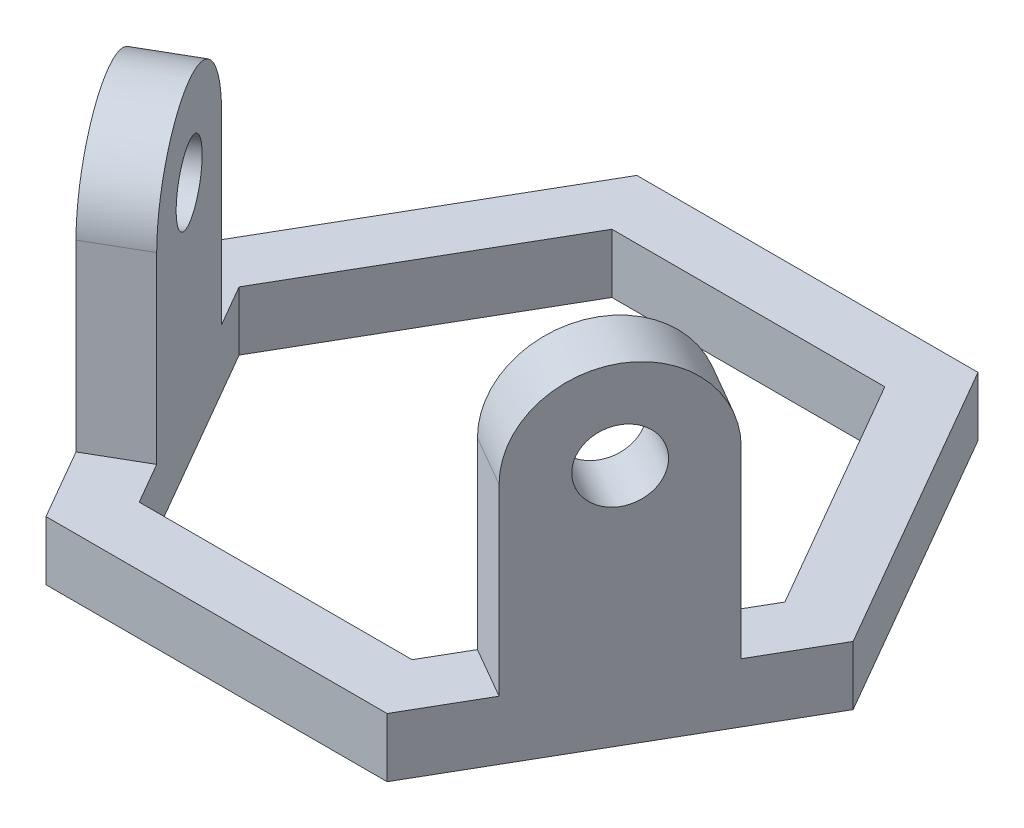
SolidWorks part; units mm, degrees
ref_plane "Front Plane" through (0, 0, 0) normal (0, 0, 1) x (1, 0, 0)
ref_plane "Top Plane" through (0, 0, 0) normal (0, 1, 0) x (1, 0, 0)
ref_plane "Right Plane" through (0, 0, 0) normal (1, 0, 0) x (0, 0, -1)
sketch "Sketch1" plane through (0, 0, 0) normal (0, 1, 0) x (1, 0, 0)
  line L0 (46.188, 0) -> (23.094, 40)
  line L1 (57.735, 0) -> (28.8675, 50)
  line L2 (28.8675, 50) -> (-28.8675, 50)
  line L3 (-28.8675, 50) -> (-57.735, 0)
  line L4 (-57.735, 0) -> (-28.8675, -50)
  line L5 (-28.8675, -50) -> (28.8675, -50)
  line L6 (28.8675, -50) -> (57.735, 0)
  line L7 (23.094, 40) -> (-23.094, 40)
  line L8 (-23.094, 40) -> (-46.188, 0)
  line L9 (-46.188, 0) -> (-23.094, -40)
  line L10 (-23.094, -40) -> (23.094, -40)
  line L11 (23.094, -40) -> (46.188, 0)
  circle A0 centre (0, 0) radius 50 construction
  dimension "D1" = 100
  dimension "D2" = 10
extrude "Boss-Extrude1" add sketch "Sketch1" along normal blind 10
sketch "Sketch2" plane through (-43.3013, 0, 25) normal (-0.866, 0, 0.5) x (0.5, 0, 0.866)
  line L0 (0, 0) -> (0, 7.0403) construction
  line L1 (0, 0) -> (0, 58.2321) construction
  line L2 (15, 41.0478) -> (15, 10)
  line L3 (-28.8675, 10) -> (28.8675, 10) construction
  line L4 (15, 10) -> (-15, 10)
  line L5 (-15, 10) -> (-15, 41.0478)
  arc A0 (15, 41.0478) -> (-15, 41.0478) centre (0, 41.0478) ccw
  circle A1 centre (0, 41.0478) radius 6
  dimension "D1" = 12
  dimension "D2" = 30
extrude "Boss-Extrude2" add sketch "Sketch2" against normal blind 10
sketch "Sketch3" plane through (43.3013, 0, 25) normal (0.866, 0, 0.5) x (0.5, 0, -0.866)
  line L0 (0, 0) -> (0, 7.0403) construction
  line L1 (0, 0) -> (0, 58.2321) construction
  line L2 (15, 41.0478) -> (15, 10)
  line L3 (15, 10) -> (-15, 10)
  line L4 (-15, 10) -> (-15, 41.0478)
  line L5 (-28.8675, 10) -> (28.8675, 10) construction
  arc A0 (15, 41.0478) -> (-15, 41.0478) centre (0, 41.0478) ccw
  circle A1 centre (0, 41.0478) radius 6
  dimension "D1" = 12
  dimension "D2" = 30
  dimension "D3" = 0
  dimension "D4" = 0
extrude "Boss-Extrude3" add sketch "Sketch3" against normal blind 10
